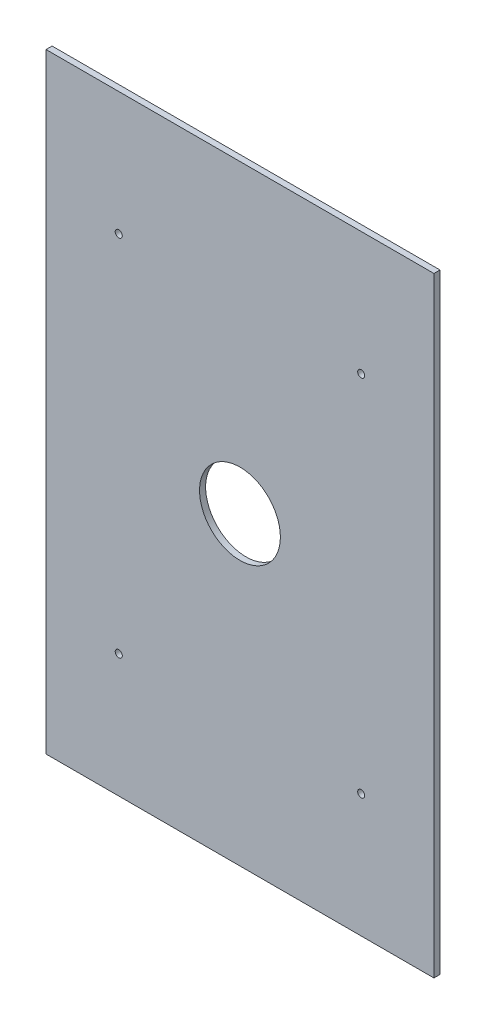
SolidWorks part; units mm, degrees
ref_plane "前视基准面" through (0, 0, 0) normal (0, 0, 1) x (1, 0, 0)
ref_plane "上视基准面" through (0, 0, 0) normal (0, 1, 0) x (1, 0, 0)
ref_plane "右视基准面" through (0, 0, 0) normal (1, 0, 0) x (0, 0, -1)
other "Configuration Table"
sketch "草图1" plane through (0, 0, 0) normal (0, 0, 1) x (1, 0, 0)
  line L0 (0, 0) -> (384, 0)
  line L1 (384, 0) -> (384, 604)
  line L2 (384, 604) -> (0, 604)
  line L3 (0, 604) -> (0, 0)
  dimension "width" = 384
  dimension "height" = 604
extrude "Recessed_top_seat" add sketch "草图1" along normal blind 6
sketch "草图2" plane through (0, 0, 6) normal (0, 0, 1) x (1, 0, 0)
  circle A0 centre (192, 302) radius 40
  dimension "diameter" = 80
  dimension "x" = 192
  dimension "y" = 302
extrude "Central_access" cut sketch "草图2" against normal through all
sketch "草图3" plane through (0, 0, 6) normal (0, 0, 1) x (1, 0, 0)
  circle A0 centre (72, 122) radius 3.5
  dimension "diameter" = 7
  dimension "x" = 72
  dimension "y" = 122
extrude "Fastener_clearance" cut sketch "草图3" against normal through all
sketch "草图4" plane through (0, 0, 6) normal (0, 0, 1) x (1, 0, 0)
  circle A0 centre (72, 482) radius 3.5
  dimension "diameter" = 7
  dimension "x" = 72
  dimension "y" = 482
extrude "切除-拉伸3" cut sketch "草图4" against normal through all
sketch "草图5" plane through (0, 0, 6) normal (0, 0, 1) x (1, 0, 0)
  circle A0 centre (312, 122) radius 3.5
  dimension "diameter" = 7
  dimension "x" = 312
  dimension "y" = 122
extrude "切除-拉伸4" cut sketch "草图5" against normal through all
sketch "草图6" plane through (0, 0, 6) normal (0, 0, 1) x (1, 0, 0)
  circle A0 centre (312, 482) radius 3.5
  dimension "diameter" = 7
  dimension "x" = 312
  dimension "y" = 482
extrude "切除-拉伸5" cut sketch "草图6" against normal through all
